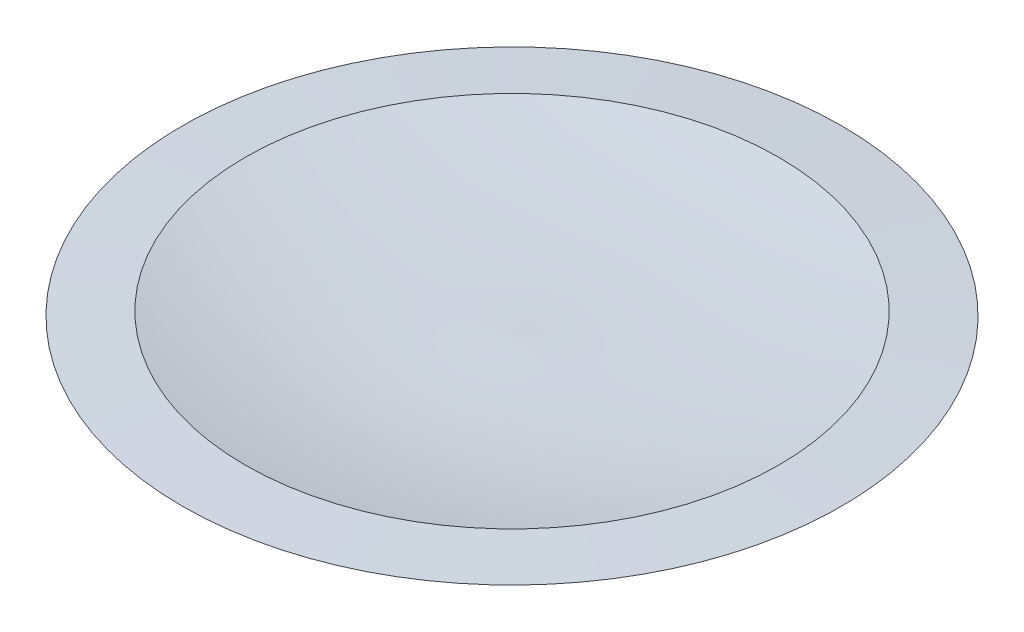
SolidWorks part; units mm, degrees
ref_plane "Front Plane" through (0, 0, 0) normal (0, 0, 1) x (1, 0, 0)
ref_plane "Top Plane" through (0, 0, 0) normal (0, 1, 0) x (1, 0, 0)
ref_plane "Right Plane" through (0, 0, 0) normal (1, 0, 0) x (0, 0, -1)
sketch "Sketch1" plane through (0, 0, 0) normal (0, 0, 1) x (1, 0, 0)
  line L0 (45.2166, 0) -> (49.1056, 3.889)
  line L1 (0, 0) -> (0, 10.4559)
  line L3 (102.7743, 18.7383) -> (127, 17.1332)
  spline S0 degree 1 poles (0, 0) (45.2166, 0) knots 0 0 1 1
  spline S1 degree 2 poles (49.1056, 3.889) (89.5035, 4.3357) (127, 17.1332) knots 0 0 0 1 1 1
  spline S2 degree 2 poles (0, 10.4559) (52.4464, 7.2043) (102.7743, 18.7383) knots 0 0 0 1 1 1
  dimension "D1" = 127
revolve "Revolve3" add sketch "Sketch1" angle 360 about L1
